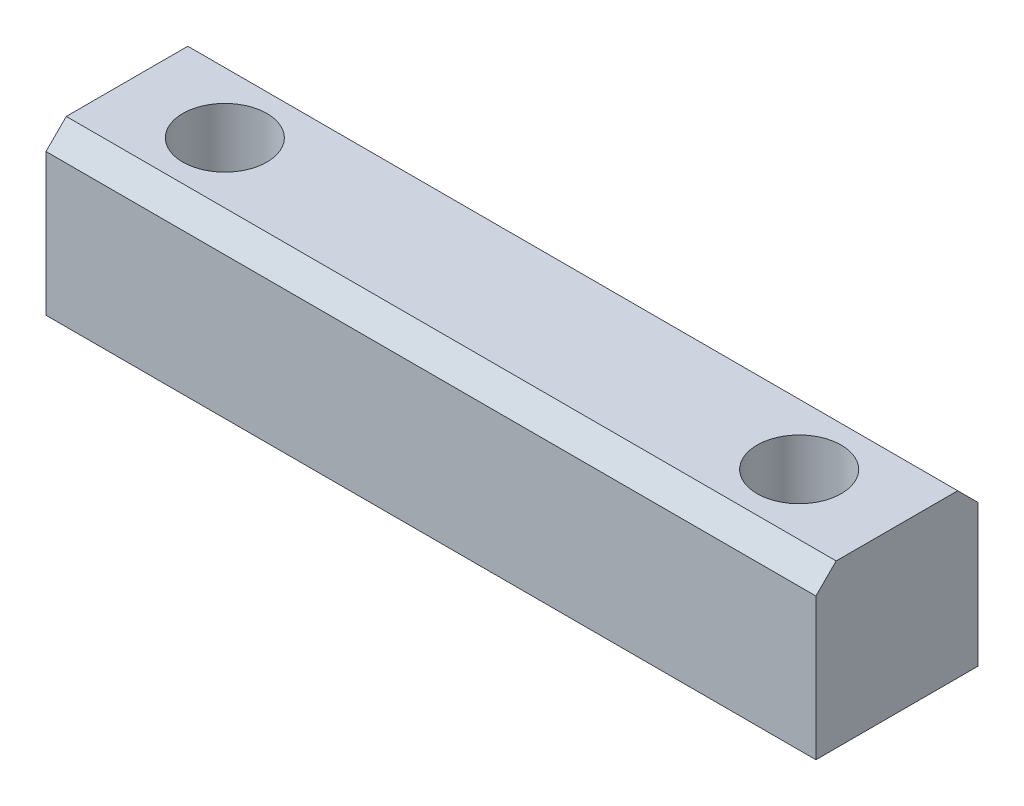
SolidWorks part; units mm, degrees
material "Low Carbon Steel"
ref_plane "Front Plane" through (0, 0, 0) normal (0, 0, 1) x (1, 0, 0)
ref_plane "Top Plane" through (0, 0, 0) normal (0, 1, 0) x (1, 0, 0)
ref_plane "Right Plane" through (0, 0, 0) normal (1, 0, 0) x (0, 0, -1)
sketch "Sketch1" plane through (0, 0, 0) normal (1, 0, 0) x (0, 0, -1)
  line L0 (-6.35, -6.35) -> (6.35, 6.35) construction
  line L1 (-6.35, 6.35) -> (6.35, 6.35)
  line L2 (-6.35, 6.35) -> (-6.35, -6.35)
  line L3 (-6.35, -6.35) -> (6.35, -6.35)
  line L4 (6.35, 6.35) -> (6.35, -6.35)
  dimension "D1" = 12.7
  dimension "D2" = 12.7
extrude "Boss-Extrude1" add sketch "Sketch1" along normal mid plane 60.325
hole_wizard "M6 Clearance Hole1" positions "Sketch3" profile "Sketch2" hole size "M6" standard "Peddi DIN" end condition through all
sketch "Sketch3" plane through (0, 6.35, 0) normal (0, 1, 0) x (1, 0, 0)
  line L0 (-22.5, 0) -> (22.5, 0) construction
  point P0 (-22.5, 0)
  point P2 (22.5, 0)
  dimension "D1" = 45
sketch "Sketch2" plane through (-22.5, 6.35, 0) normal (1, 0, 0) x (0, 0, 1)
  line L0 (0, 0) -> (0, 12.7)
  line L1 (0, 12.7) -> (3.3, 12.7)
  line L2 (3.3, 12.7) -> (3.3, 0)
  line L5 (3.3, 0) -> (0, 0)
  line L11 (0, -6.35) -> (0, 107.95) construction
  dimension "Thru Hole Dia." = 6.6
  dimension "Thru Hole Depth" = 12.7
chamfer "Chamfer1" distance 1.5875 angle 45 2 edges at (0, 6.35, -6.35) (0, 6.35, 6.35)
other "Freeze***"
